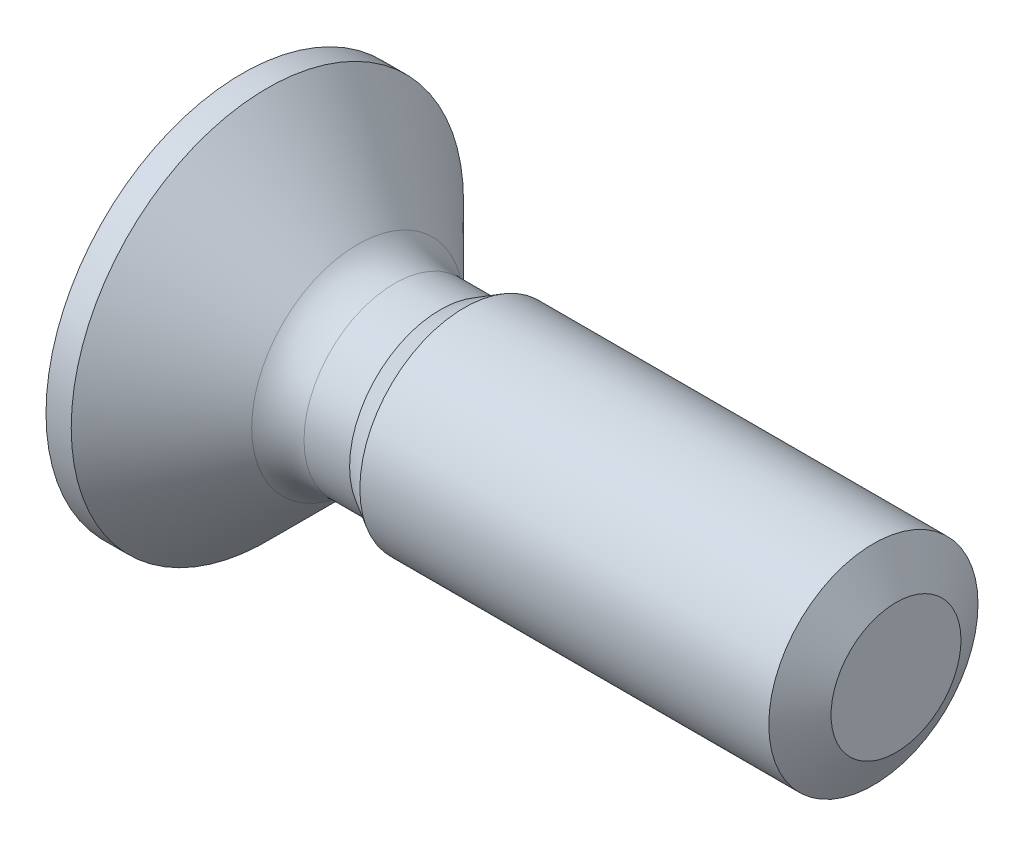
SolidWorks part; units mm, degrees
revolve "基体-旋转" add sketch "草图1" angle 360 about L0
sketch "草图1" plane through (0, 0, 0) normal (0, 0, 1) x (1, 0, 0)
  line L0 (0, 0) -> (4.4175, 0) construction
  line L1 (0, 0) -> (0, 1.5)
  line L2 (0, 1.5) -> (0.1928, 1.5)
  line L3 (0.1928, 1.5) -> (0.8828, 0.81)
  line L4 (1.1657, 0.6928) -> (1.5143, 0.6928)
  line L5 (1.5143, 0.6928) -> (1.7, 0.8)
  line L6 (1.7, 0.8) -> (5, 0.8)
  line L7 (5, 0.8) -> (5, 0)
  line L8 (0, 0) -> (5, 0)
  arc A0 (1.1657, 0.6928) -> (0.8828, 0.81) centre (1.1657, 1.0928) cw
  point P12 (1, 0.6928)
  dimension "D2" = 0.4
  dimension "D1" = 1.3856
  dimension "d" = 1.6
  dimension "dk" = 3
  dimension "k" = 1
  dimension "D5" = 45
  dimension "a" = 0.7
  dimension "l" = 5
  dimension "D8" = 30
cosmetic thread "装饰螺纹线2" parameters "D1"=3.3, "D2"=1.25
material "4.8级"
ref_plane "前视" through (0, 0, 0) normal (0, 0, 1) x (1, 0, 0)
ref_plane "上视" through (0, 0, 0) normal (0, 1, 0) x (1, 0, 0)
ref_plane "右视" through (0, 0, 0) normal (1, 0, 0) x (0, 0, -1)
sketch "尺寸草图" plane through (0, 0, 0) normal (0, 0, 1) x (1, 0, 0)
  line L0 (0, 0) -> (5, 0)
  point P3 (1, 0)
  point P4 (0.7, 0)
  point P5 (1.6, 0)
  point P6 (3, 0)
  point P7 (3.4, 0)
  point P8 (3.5943, 0)
  point P9 (4.6, 0)
  point P10 (4.1, 0)
  point P11 (4.65, 0)
  dimension "d" = 1.6
  dimension "dk" = 3
  dimension "k" = 1
  dimension "a" = 0.7
  dimension "l" = 5
  dimension "r" = 0.4
  dimension "m" = 1.6
  dimension "h" = 0.9
  dimension "p" = 0.35
sketch "草图2" plane through (0, 0, 0) normal (0, 0, 1) x (1, 0, 0)
  line L0 (4.8269, 0.8) -> (5.1769, 0.8)
  line L1 (5.1769, 0.8) -> (5, 0.4969)
  line L2 (5, 0.4969) -> (4.8269, 0.8)
  line L3 (5, -0.8) -> (5, 0.8) construction
  line L6 (0, 0) -> (-0.4315, 0) construction
  dimension "D2" = 0.3031
  dimension "D3" = 0.8
  dimension "D4" = 60
revolve "切除-旋转1" cut sketch "草图2" angle 360 about L6
pattern_linear "阵列(线性)1" [suppressed] count 9 spacing 0.35 along (1, 0, 0)
sketch "草图3" plane through (0, 0, 0) normal (-1, 0, 0) x (0, 0, 1)
  line L0 (0, 0) -> (1.6329, 0) construction
  line L1 (0, 0) -> (0, 0.8499) construction
  line L2 (-0.8, 0.175) -> (0.8, 0.175)
  line L3 (-0.8, 0.175) -> (-0.8, -0.175)
  line L4 (-0.8, -0.175) -> (0.8, -0.175)
  line L5 (0.8, 0.175) -> (0.8, -0.175)
  dimension "m" = 1.6
  dimension "D1" = 0.35
ref_plane "基准面1" through (0.9, 0, 0) normal (-1, 0, 0) x (0, 0, 1)
sketch "草图4" plane through (0.9, 0, 0) normal (-1, 0, 0) x (0, 0, 1)
  point P0 (0, 0)
loft "切除-放样1" cut profiles "草图3", "草图4"
pattern_circular "阵列(圆周)1" count 2 every 90 about axis through (0, 0, 0) along (1, 0, 0) of "切除-放样1"
equation "\"l@草图1\" = \"l@尺寸草图\""
equation "\"k@草图1\" = \"k@尺寸草图\""
equation "\"a@草图1\" = \"a@尺寸草图\""
equation "\"d@草图1\" = \"d@尺寸草图\""
equation "\"dk@草图1\" = \"dk@尺寸草图\""
equation "\"D2@草图1\" = \"r@尺寸草图\""
equation "\"m@草图3\" = \"m@尺寸草图\""
equation "\"h@基准面1\" = \"h@尺寸草图\""
equation "\"D3@阵列(线性)1\" = \"p@尺寸草图\""
equation "\"D3@草图2\" = \"d@草图1\" / 2"
equation "\"D1@装饰螺纹线2\" = \"l@草图1\" - \"k@草图1\" - \"a@草图1\""
equation "\"D2@装饰螺纹线2\" = \"d@尺寸草图\"- \"p@尺寸草图\""
equation "\"D1@阵列(线性)1\" = (  \"l@草图1\" - \"k@草图1\" - \"a@草图1\" )  / \"p@尺寸草图\""
equation "\"D1@草图3\" = \"p@尺寸草图\""
equation "\"D1@草图1\" = \"d@尺寸草图\"*0.866"
equation "\"D2@草图2\" = \"p@尺寸草图\"*0.866"
equation "\"D1@草图2\" = \"p@尺寸草图\""
